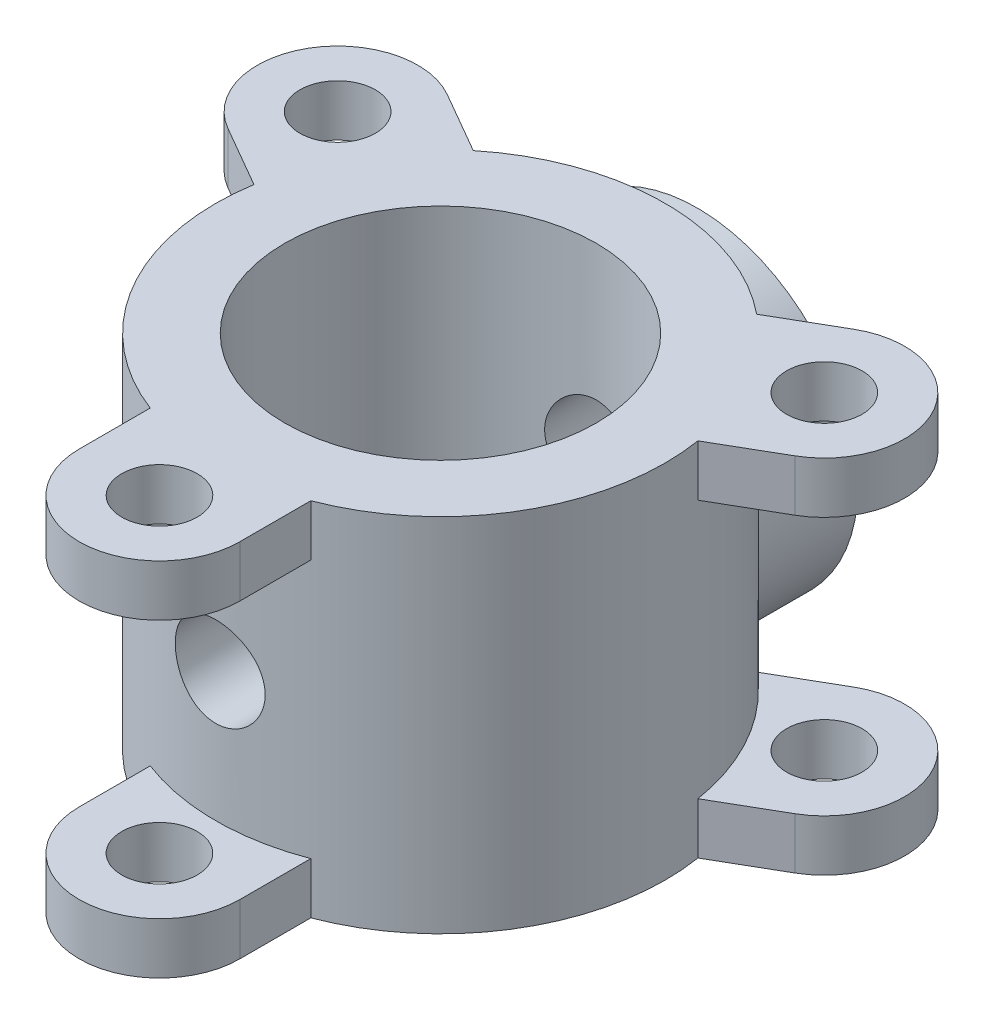
SolidWorks part; units mm, degrees
material "6061 Alloy"
ref_plane "Front Plane" through (0, 0, 0) normal (0, 0, 1) x (1, 0, 0)
ref_plane "Top Plane" through (0, 0, 0) normal (0, 1, 0) x (1, 0, 0)
ref_plane "Right Plane" through (0, 0, 0) normal (1, 0, 0) x (0, 0, -1)
sketch "Sketch3" plane through (0, 0, 0) normal (0, 1, 0) x (1, 0, 0)
  circle A0 centre (0, 0) radius 140
  dimension "D1" = 280
extrude "Boss-Extrude1" add sketch "Sketch3" along normal blind 225
sketch "Sketch4" plane through (0, 0, 0) normal (0, -1, 0) x (1, 0, 0)
  circle A0 centre (0, 0) radius 97
  dimension "D1" = 194
extrude "Cut-Extrude1" cut sketch "Sketch4" against normal through all
sketch "Sketch10" plane through (0, 0, 0) normal (0, -1, 0) x (1, 0, 0)
  line L1 (-50, 175) -> (-50, 130.767)
  line L2 (50, 175) -> (50, 130.767)
  arc A3 (-50, 175) -> (50, 175) centre (0, 175) cw
  arc A4 (-50, 130.767) -> (50, 130.767) centre (0, 0) cw
  dimension "D2" = 50
extrude "Boss-Extrude3" add sketch "Sketch10" against normal blind 32
sketch "Sketch11" plane through (0, 0, 0) normal (0, -1, 0) x (1, 0, 0)
  circle A0 centre (0, 175) radius 23.5
  dimension "D1" = 47
extrude "Cut-Extrude3" cut sketch "Sketch11" against normal through all
pattern_circular "CirPattern15" count 3 over 360 about axis through (0, 0, 0) along (0, 1, 0) of "Boss-Extrude3", "Cut-Extrude3"
ref_plane "Plane1" through (0, 112.5, 0) normal (0, 1, 0) x (1, 0, 0)
mirror "Mirror6" about plane through (0, 112.5, 0) normal (0, 1, 0) of "CirPattern15", "Boss-Extrude3", "Cut-Extrude3"
ref_plane "Plane2" through (0, 0, 0) normal (0, 0, 1) x (1, 0, 0)
sketch "Sketch16" plane through (0, 0, 0) normal (0, 0, 1) x (1, 0, 0)
  line L0 (140, 0) -> (140, 225) construction
  circle A0 centre (0, 112.5) radius 100
  dimension "D1" = 200
  dimension "D3" = 112.5
  dimension "D4" = 140
extrude "Boss-Extrude4" add sketch "Sketch16" against normal blind 160
sketch "Sketch17" plane through (0, 0, -160) normal (0, 0, -1) x (-1, 0, 0)
  circle A0 centre (0, 112.5) radius 50
  dimension "D1" = 100
extrude "Cut-Extrude4" cut sketch "Sketch17" against normal blind 25
sketch "Sketch18" plane through (0, 0, -135) normal (0, 0, -1) x (-1, 0, 0)
  circle A0 centre (0, 112.5) radius 28
  dimension "D1" = 56
extrude "Cut-Extrude5" cut sketch "Sketch18" against normal through all
sketch "Sketch19" plane through (0, 0, -160) normal (0, 0, -1) x (-1, 0, 0)
  circle A0 centre (0, 112.5) radius 75
  circle A1 centre (0, 187.5) radius 12
  circle A2 centre (162.3798, -93.75) radius 12
  circle A3 centre (-162.3798, -93.75) radius 12
  circle A4 centre (64.9519, 75) radius 12
  circle A5 centre (-64.9519, 75) radius 12
  point P12 (0, 0)
  point P17 (0, 112.5)
  dimension "D1" = 150
  dimension "D2" = 24
  dimension "D3" = 3
  dimension "D4" = 3
extrude "Cut-Extrude6" cut sketch "Sketch19" against normal blind 15 contours A5 | A1 | A4
sketch "Sketch20" plane through (0, 0, 0) normal (0, -1, 0) x (1, 0, 0)
  circle A0 centre (0, 0) radius 97
extrude "Cut-Extrude7" cut sketch "Sketch20" against normal through all
